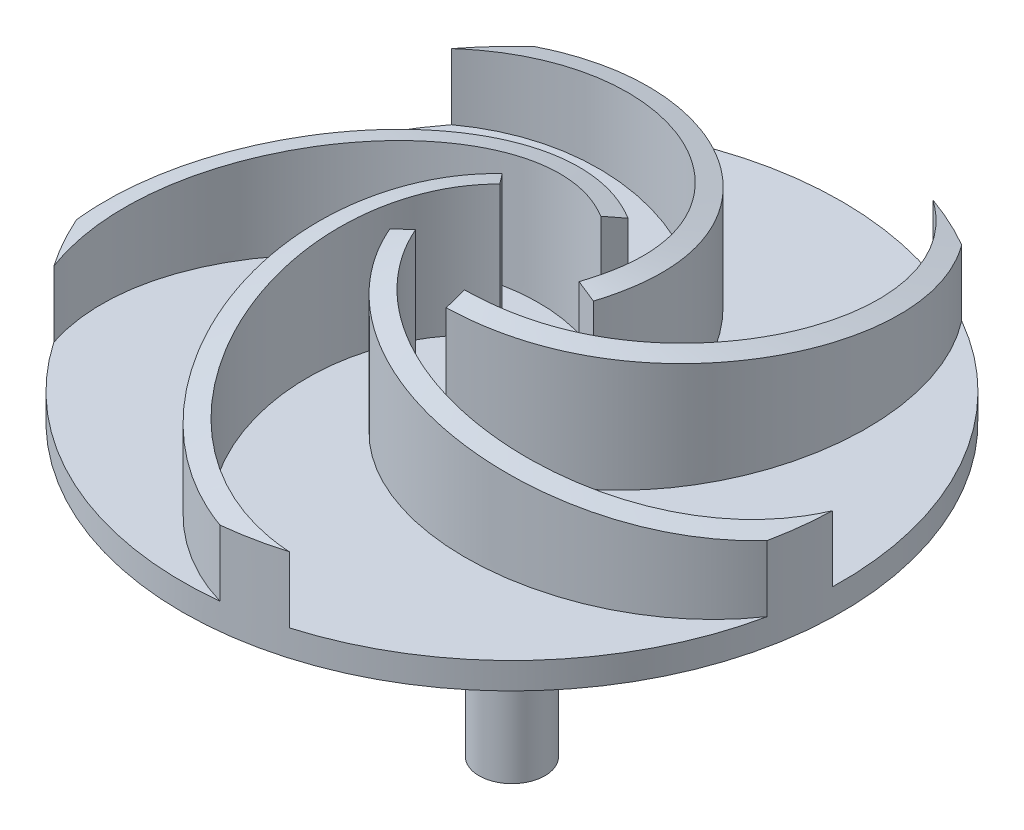
SolidWorks part; units mm, degrees
ref_plane "Front Plane" through (0, 0, 0) normal (0, 0, 1) x (1, 0, 0)
ref_plane "Top Plane" through (0, 0, 0) normal (0, 1, 0) x (1, 0, 0)
ref_plane "Right Plane" through (0, 0, 0) normal (1, 0, 0) x (0, 0, -1)
sketch "Sketch1" plane through (0, 0, 0) normal (0, 1, 0) x (1, 0, 0)
  circle A0 centre (0, 0) radius 25
  dimension "D1" = 50
extrude "Boss-Extrude1" add sketch "Sketch1" along normal blind 2
sketch "Sketch6" plane through (0, 2, 0) normal (0, 1, 0) x (1, 0, 0)
  line L0 (-5.7493, -3.5145) -> (-4.3579, -2.9543)
  circle A1 centre (0, 0) radius 6 construction
  circle A2 centre (0, 0) radius 25 construction
  arc A3 (24.9909, -0.6741) -> (24.4716, -5.1127) centre (0, 0) cw
  spline S0 degree 1 poles (25.0627, -0.4446) (-4.3579, -2.9543) knots 0 0 1 1 construction
  spline S1 degree 3 poles (25.7803, -0.6625) (21.6404, -14.2953) (0.0983, -16.0311) (-5.0536, -3.2344) knots 0 0 0 0 1 1 1 1 construction
  spline S2 degree 3 poles (25.0627, -0.4446) (24.9415, -0.8439) (24.6609, -1.6391) (23.9856, -3.1188) (22.9273, -4.8072) (21.3623, -6.5622) (18.9387, -8.5421) (15.3904, -10.3257) (10.688, -11.311) (5.9458, -11.1024) (2.2991, -9.9186) (-0.2437, -8.3638) (-1.92, -6.8935) (-3.0916, -5.407) (-3.8701, -4.0639) (-4.2082, -3.326) (-4.3579, -2.9543) knots 0 0 0 0 0.03125 0.0625 0.125 0.1875 0.25 0.375 0.5 0.625 0.75 0.8125 0.875 0.9375 0.96875 1 1 1 1 only from (24.9909, -0.6741) to (-4.3579, -2.9543)
  spline S3 degree 1 poles (26.498, -0.8804) (-5.7493, -3.5145) knots 0 0 1 1 construction
  spline S4 degree 3 poles (26.498, -0.8804) (26.3639, -1.322) (26.054, -2.2007) (25.3054, -3.8411) (24.1316, -5.7133) (22.4022, -7.6519) (19.741, -9.8246) (15.8842, -11.7596) (10.8135, -12.821) (5.6878, -12.5982) (1.6922, -11.3067) (-1.1345, -9.5799) (-3.0133, -7.9327) (-4.3313, -6.2609) (-5.2048, -4.7532) (-5.5821, -3.9299) (-5.7493, -3.5145) knots 0 0 0 0 0.03125 0.0625 0.125 0.1875 0.25 0.375 0.5 0.625 0.75 0.8125 0.875 0.9375 0.96875 1 1 1 1 only from (24.4716, -5.1127) to (-5.7493, -3.5145)
  circle M3 centre (0, 0) radius 25
  dimension "D1" = 12
  dimension "D4" = 0.6155
  dimension "D5" = 12.8473
  dimension "D6" = 24.4716
  dimension "D7" = 24.9909
  dimension "D8" = 25.7803
  dimension "D9" = 4.3579
  dimension "D10" = 5.0536
  dimension "D2" = 0.75
  dimension "D3" = 0.75
extrude "Boss-Extrude3" add sketch "Sketch6" along normal blind 11 contours S4 S2 L0 M3
pattern_circular "CirPattern2" count 5 over 360 of "Boss-Extrude3"
sketch "Sketch7" plane through (0, 0, 0) normal (1, 0, 0) x (0, 0, -1)
  line L0 (25, 7) -> (25, 13)
  line L1 (25, 13) -> (1, 13)
  line L2 (21.694, 13) -> (-6.554, 13) construction
  line L3 (1, 13) -> (25, 7)
  line L4 (0, 0) -> (0, 5.0173) construction
  dimension "D1" = 5
  dimension "D2" = 1
revolve "Cut-Revolve7" cut sketch "Sketch7" angle 360 about L4
sketch "Sketch8" plane through (0, 0, 0) normal (0, -1, 0) x (1, 0, 0)
  circle A0 centre (0, 0) radius 3
  dimension "D1" = 6
extrude "Boss-Extrude4" add sketch "Sketch8" along normal blind 22
sketch "Sketch9" plane through (0, 0, 0) normal (0, 0, 1) x (1, 0, 0)
  line L0 (-3, -11) -> (-2.5, -12)
  line L1 (-3, 0) -> (-3, -22) construction
  line L2 (-2.5, -12) -> (-2.5, -22)
  line L3 (-3, -22) -> (3, -22) construction
  line L4 (-2.5, -22) -> (-3, -22)
  line L5 (-3, -22) -> (-3, -11)
  line L6 (0, 0) -> (0, -22) construction
  dimension "D1" = 11
  dimension "D2" = 0.5
  dimension "D3" = 1
revolve "Cut-Revolve8" cut sketch "Sketch9" angle 360 about L6
